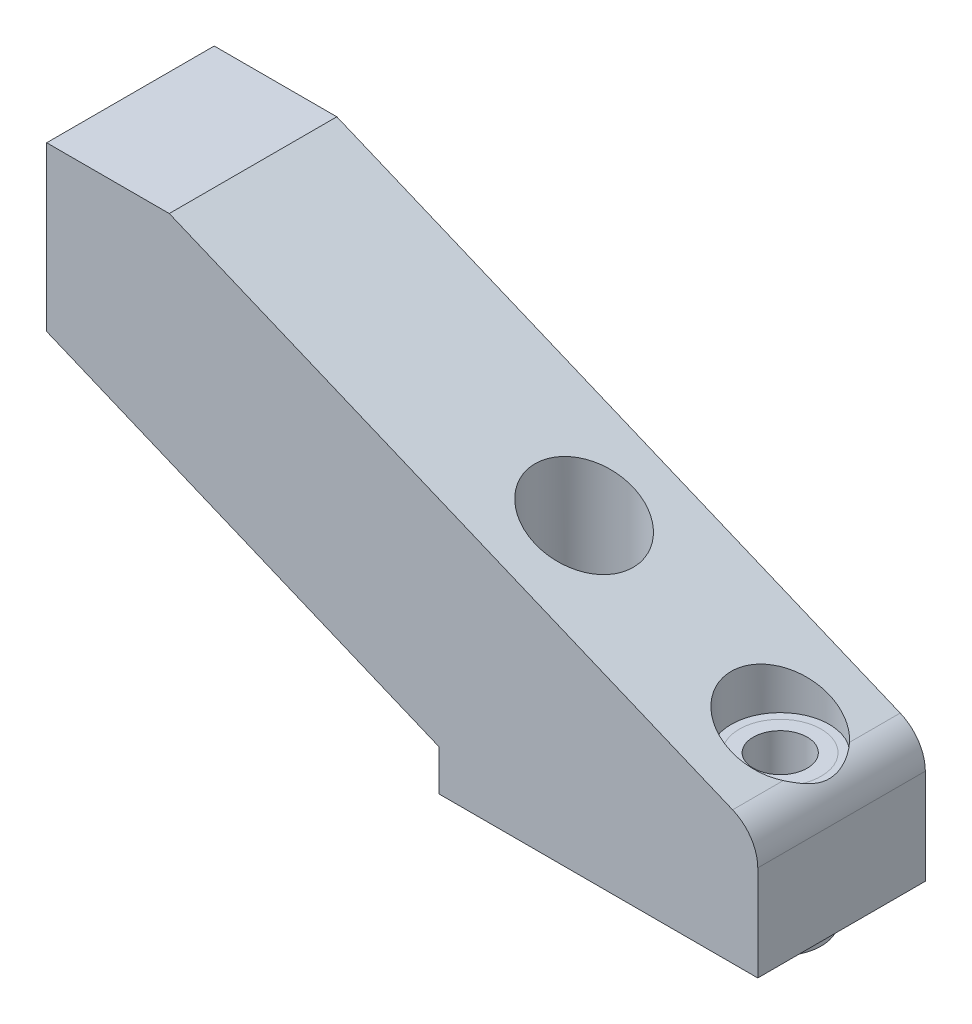
SolidWorks part; units mm, degrees
material "1.0036 (S235JRG1)"
ref_plane "Front Plane" through (0, 0, 0) normal (0, 0, 1) x (1, 0, 0)
ref_plane "Top Plane" through (0, 0, 0) normal (0, 1, 0) x (1, 0, 0)
ref_plane "Right Plane" through (0, 0, 0) normal (1, 0, 0) x (0, 0, -1)
sketch "Sketch1" plane through (0, 0, 0) normal (0, 0, 1) x (1, 0, 0)
  line L0 (0, 0) -> (0, 6.6667)
  line L1 (-3.0769, 11.2821) -> (-72, 40)
  line L2 (-72, 40) -> (-87, 40)
  line L3 (-87, 40) -> (-87, 20)
  line L5 (-87, 20) -> (-39, 0)
  line L6 (-39, 0) -> (-39, -5)
  line L7 (-39, -5) -> (0, -5)
  line L8 (0, -5) -> (0, 0)
  arc A0 (0, 6.6667) -> (-3.0769, 11.2821) centre (-5, 6.6667) ccw
  point P8 (0, 10)
  point P10 (-39, 0)
  point P11 (-87, 0)
  point P14 (-87, 40)
  point P21 (-87, 40)
  dimension "D5" = 5
  dimension "D7" = 39
  dimension "D8" = 5
  dimension "D1" = 87
  dimension "D2" = 40
  dimension "D3" = 15
  dimension "D4" = 10
  dimension "D6" = 5
  dimension "D9" = 48
  dimension "D10" = 20
extrude "Boss-Extrude1" add sketch "Sketch1" along normal blind 20.5
sketch "Sketch2" plane through (0, 0, 0) normal (0, 1, 0) x (1, 0, 0)
  line L0 (0, -10.25) -> (-31.5, -10.25) construction
  line L1 (0, -20.5) -> (0, 0) construction
  circle A0 centre (-7.5, -10.25) radius 3.3
  circle A1 centre (-31.5, -10.25) radius 3.3
  dimension "D1" = 6.6
  dimension "D2" = 7.5
  dimension "D3" = 24
extrude "Cut-Extrude1" cut sketch "Sketch2" along normal through all and the other way blind 10
sketch "Sketch3" plane through (0, 40, 0) normal (0, 1, 0) x (1, 0, 0)
  circle A0 centre (-7.5, -10.25) radius 6
  circle A1 centre (-31.5, -10.25) radius 6
  dimension "D1" = 12
extrude "Cut-Extrude2" cut sketch "Sketch3" against normal blind 30
sketch "Sketch4" plane through (0, -5, 0) normal (0, -1, 0) x (1, 0, 0)
  circle A0 centre (-31.5, 10.25) radius 5
  circle A1 centre (-7.5, 10.25) radius 5
  circle A2 centre (-31.5, 10.25) radius 3.25
  circle A3 centre (-7.5, 10.25) radius 3.25
  dimension "D1" = 10
  dimension "D2" = 6.5
extrude "Boss-Extrude2" add sketch "Sketch4" along normal blind 3
sketch "Sketch5" plane through (0, 10, 0) normal (0, 1, 0) x (1, 0, 0)
  circle A0 centre (-7.5, -10.25) radius 5
  circle A1 centre (-31.5, -10.25) radius 5
  dimension "D1" = 10
split line "Split Line1"
ref_plane "Plane1" through (0, -5, 0) normal (0, 1, 0) x (1, 0, 0)
